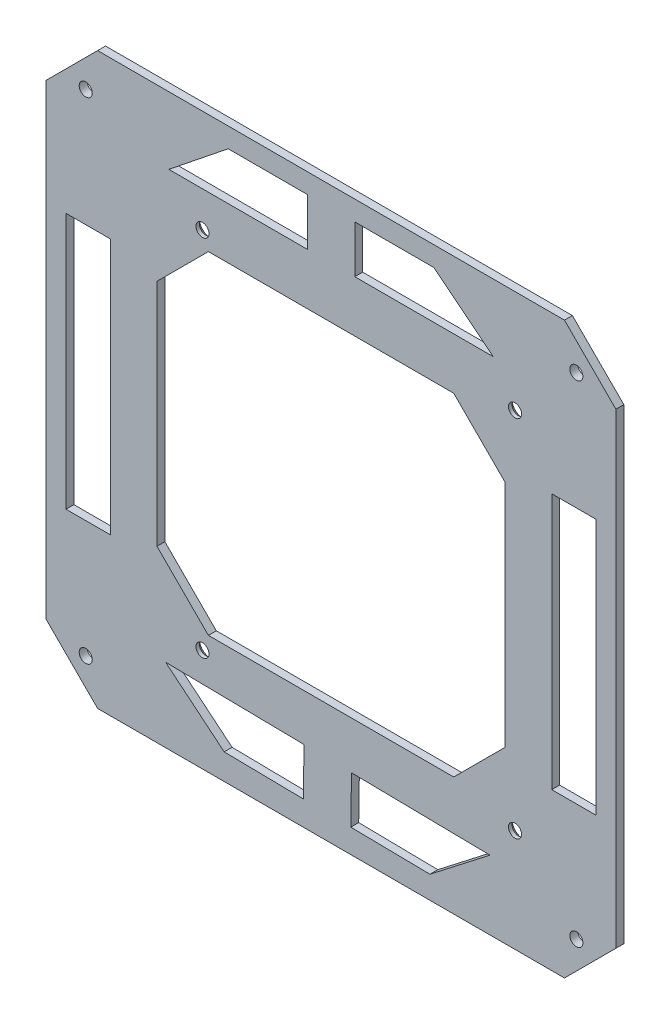
SolidWorks part; units mm, degrees
material "碳纤维板_1600kg_m3"
ref_plane "前视基准面" through (0, 0, 0) normal (0, 0, 1) x (1, 0, 0)
ref_plane "上视基准面" through (0, 0, 0) normal (0, 1, 0) x (1, 0, 0)
ref_plane "右视基准面" through (0, 0, 0) normal (1, 0, 0) x (0, 0, -1)
other "Configuration Table"
sketch "草图1" plane through (0, 0, 0) normal (0, 0, 1) x (1, 0, 0)
  line L0 (16, 72) -> (16, 67) construction
  line L1 (-72, 1.0933) -> (72, 0) construction
  line L2 (0, 72) -> (0, -72) construction
  line L3 (-26, 67) -> (-6, 67)
  line L4 (-41, 55) -> (-26, 67)
  line L5 (-6, 55) -> (-41, 55)
  line L6 (-6, 67) -> (-6, 55)
  line L7 (4.9903, -65.9902) -> (5.1725, -53.9916)
  line L8 (24.988, -66.2938) -> (4.9903, -65.9902)
  line L9 (40.1685, -54.523) -> (24.988, -66.2938)
  line L10 (5.1725, -53.9916) -> (40.1685, -54.523)
  line L11 (-7.0083, -65.808) -> (-6.8261, -53.8094)
  line L12 (-6.8261, -53.8094) -> (-41.8221, -53.2779)
  line L13 (-41.8221, -53.2779) -> (-27.006, -65.5043)
  line L14 (-27.006, -65.5043) -> (-7.0083, -65.808)
  line L15 (67, 0) -> (72, 0) construction
  line L28 (55.787, 32.3856) -> (67, 32.3856)
  line L29 (55.787, 32.3856) -> (55.787, -32.3856)
  line L30 (55.787, -32.3856) -> (67, -32.3856)
  line L31 (67, 32.3856) -> (67, -32.3856)
  line L32 (-67, 32.3856) -> (-67, -32.3856)
  line L33 (-55.787, -32.3856) -> (-67, -32.3856)
  line L34 (-55.787, 32.3856) -> (-55.787, -32.3856)
  line L35 (-55.787, 32.3856) -> (-67, 32.3856)
  line L84 (-72, -72) -> (72, -72)
  line L85 (72, -72) -> (72, 72)
  line L86 (72, 72) -> (-72, 72)
  line L87 (-72, 72) -> (-72, -72)
  line L88 (-44, -42) -> (44, -42)
  line L89 (44, -42) -> (44, 42)
  line L90 (44, 42) -> (-44, 42)
  line L91 (-44, 42) -> (-44, -42)
  line L116 (6, 55) -> (41, 55)
  line L117 (41, 55) -> (26, 67)
  line L118 (26, 67) -> (6, 67)
  line L119 (6, 67) -> (6, 55)
  circle A16 centre (-62, -62) radius 1.65
  circle A17 centre (-62, 62) radius 1.65
  circle A18 centre (62, -62) radius 1.65
  circle A19 centre (62, 62) radius 1.65
  circle A20 centre (-32.5, -46) radius 1.65
  circle A21 centre (-32.5, 46) radius 1.65
  circle A22 centre (46.5, -46) radius 1.65
  circle A23 centre (46.5, 46) radius 1.65
  point P0 (0, 42)
  dimension "D1" = 30
  dimension "D2" = 30
  dimension "D3" = 28
  dimension "D4" = 28
  dimension "D5" = 5
  dimension "D6" = 90
  dimension "D7" = 35
  dimension "D8" = 5
  dimension "D9" = 144
extrude "几何镂空托板_原装79x92孔距" add sketch "草图1" along normal blind 2
sketch "草图2" plane through (0, 0, 0) normal (0, 0, 1) x (1, 0, 0)
  circle A0 centre (-32.5, -46) radius 2.75
  circle A1 centre (-32.5, 46) radius 2.75
  circle A2 centre (46.5, -46) radius 2.75
  circle A3 centre (46.5, 46) radius 2.75
extrude "M3沉头四孔_D5p5_深1p1_90度" cut sketch "草图2" along normal blind 1.1 draft 45
chamfer "倒角1" distance 13 angle 45 8 edges at (-72, -72, 1) (72, -72, 1) (72, 72, 1) (-72, 72, 1) (-44, -42, 1) (44, -42, 1) (44, 42, 1) (-44, 42, 1)
